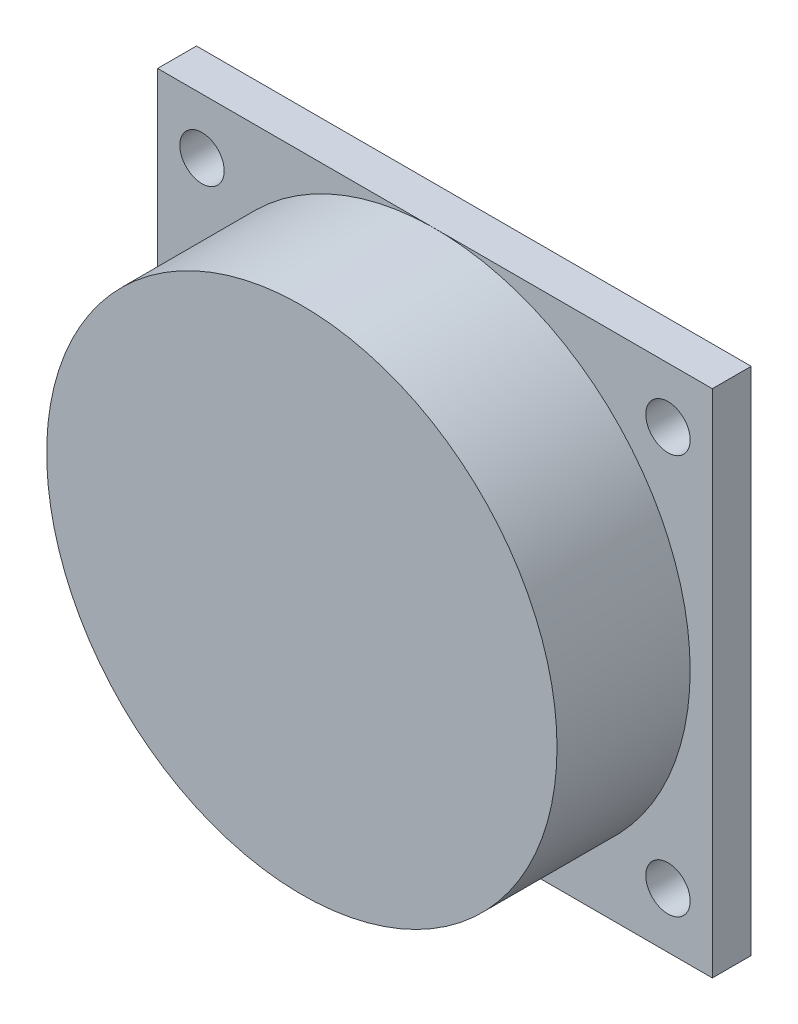
SolidWorks part; units mm, degrees
material "Custom Plastic"
ref_plane "Front Plane" through (0, 0, 0) normal (0, 0, 1) x (1, 0, 0)
ref_plane "Top Plane" through (0, 0, 0) normal (0, 1, 0) x (1, 0, 0)
ref_plane "Right Plane" through (0, 0, 0) normal (1, 0, 0) x (0, 0, -1)
sketch "Sketch1" plane through (0, 0, 0) normal (0, 0, 1) x (1, 0, 0)
  circle A0 centre (0, 0) radius 10.25
  circle A1 centre (0, 0) radius 11.5
  dimension "D1" = 20.5
  dimension "D2" = 23
extrude "Boss-Extrude1" add sketch "Sketch1" along normal blind 5.5
sketch "Sketch2" plane through (0, 0, 5.5) normal (0, 0, 1) x (1, 0, 0)
  circle A0 centre (0, 0) radius 11.5
extrude "Boss-Extrude2" add sketch "Sketch2" along normal blind 0.5
sketch "Sketch3" plane through (0, 0, 0) normal (0, 0, -1) x (-1, 0, 0)
  line L1 (12.5, -11.5) -> (-12.5, -11.5)
  line L2 (12.5, -11.5) -> (12.5, 11.5)
  line L3 (12.5, 11.5) -> (-12.5, 11.5)
  line L4 (-12.5, -11.5) -> (-12.5, 11.5)
  line L5 (12.5, -11.5) -> (-12.5, 11.5) construction
  line L6 (12.5, 11.5) -> (-12.5, -11.5) construction
  circle A0 centre (0, 0) radius 10.25
  dimension "D1" = 25
  dimension "D2" = 23
  dimension "D3" = 12.5
  dimension "D4" = 11.5
extrude "Boss-Extrude3" add sketch "Sketch3" along normal blind 1.75 separate body
sketch "Sketch4" plane through (0, -11.5, 0) normal (0, -1, 0) x (1, 0, 0)
  line L0 (12.5, -1.75) -> (-12.5, -1.75) construction
  line L1 (-2.635, -1.75) -> (2.6565, -1.75)
  line L2 (-2.635, -1.75) -> (-2.635, -1.5106)
  line L3 (-2.635, -1.5106) -> (2.6565, -1.5106)
  line L4 (2.6565, -1.75) -> (2.6565, -1.5106)
extrude "Cut-Extrude1" cut sketch "Sketch4" against normal blind 5
hole_wizard "Tap Drill for M2x0.4 Tap1" positions "Sketch6" profile "Sketch5" hole size "M2x0.4" standard "ANSI Metric" end condition through all
sketch "Sketch6" plane through (0, 0, 0) normal (0, 0, 1) x (1, 0, 0)
  line L0 (-12.5, -11.5) -> (-12.5, 11.5) construction
  line L1 (-12.5, 11.5) -> (12.5, 11.5) construction
  line L2 (12.5, 11.5) -> (12.5, -11.5) construction
  line L3 (12.5, -11.5) -> (-12.5, -11.5) construction
  line L4 (-12.5, 11) -> (-12.5, -11) construction
  line L5 (12.5, -11) -> (-12.5, -11) construction
  point P0 (-10.5, 9)
  point P2 (10.5, 9)
  point P4 (10.5, -9)
  point P15 (-10.5, -8.5)
  dimension "D1" = 2
  dimension "D2" = 2.5
  dimension "D3" = 2.5
  dimension "D4" = 2
  dimension "D5" = 2
  dimension "D6" = 2.5
  dimension "D7" = 2
  dimension "D8" = 2.5
sketch "Sketch5" plane through (-10.5, 9, 0) normal (1, 0, 0) x (0, -1, 0)
  line L0 (0, 0) -> (0, 1.75)
  line L1 (0, 1.75) -> (1, 1.75)
  line L2 (1, 1.75) -> (1, 0)
  line L5 (1, 0) -> (0, 0)
  line L11 (0, -6.35) -> (0, 107.95) construction
  dimension "Thru Hole Dia." = 2
  dimension "Thru Hole Depth" = 1.75
